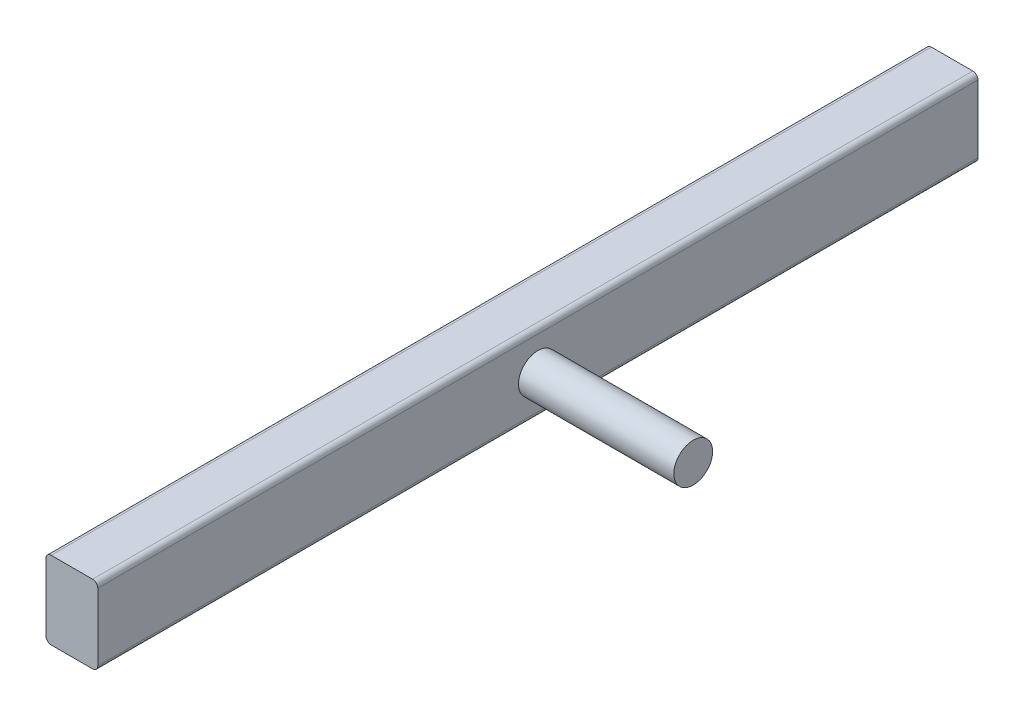
SolidWorks part; units mm, degrees
ref_plane "Front Plane" through (0, 0, 0) normal (0, 0, 1) x (1, 0, 0)
ref_plane "Top Plane" through (0, 0, 0) normal (0, 1, 0) x (1, 0, 0)
ref_plane "Right Plane" through (0, 0, 0) normal (1, 0, 0) x (0, 0, -1)
sketch "Sketch1" plane through (0, 0, 0) normal (0, 0, 1) x (1, 0, 0)
  line L0 (-1000, 0) -> (49000, 0) construction
  line L1 (0, -1000) -> (0, 49000) construction
  line L3 (-5, 7.5) -> (5, 7.5)
  line L4 (-5, 7.5) -> (-5, -7.5)
  line L5 (-5, -7.5) -> (5, -7.5)
  line L6 (5, 7.5) -> (5, -7.5)
  dimension "D1" = 15
  dimension "D2" = 10
extrude "Boss-Extrude1" add sketch "Sketch1" along normal mid plane 170
sketch "Sketch2" plane through (5, 0, 0) normal (1, 0, 0) x (0, 0, -1)
  circle A0 centre (0, 0) radius 3.75
  dimension "D1" = 7.5
extrude "Boss-Extrude2" add sketch "Sketch2" along normal blind 30
fillet "Fillet2" radius 1 4 edges at (-5, -7.5, 0) (-5, 7.5, 0) (5, -7.5, 0) (5, 7.5, 0)
